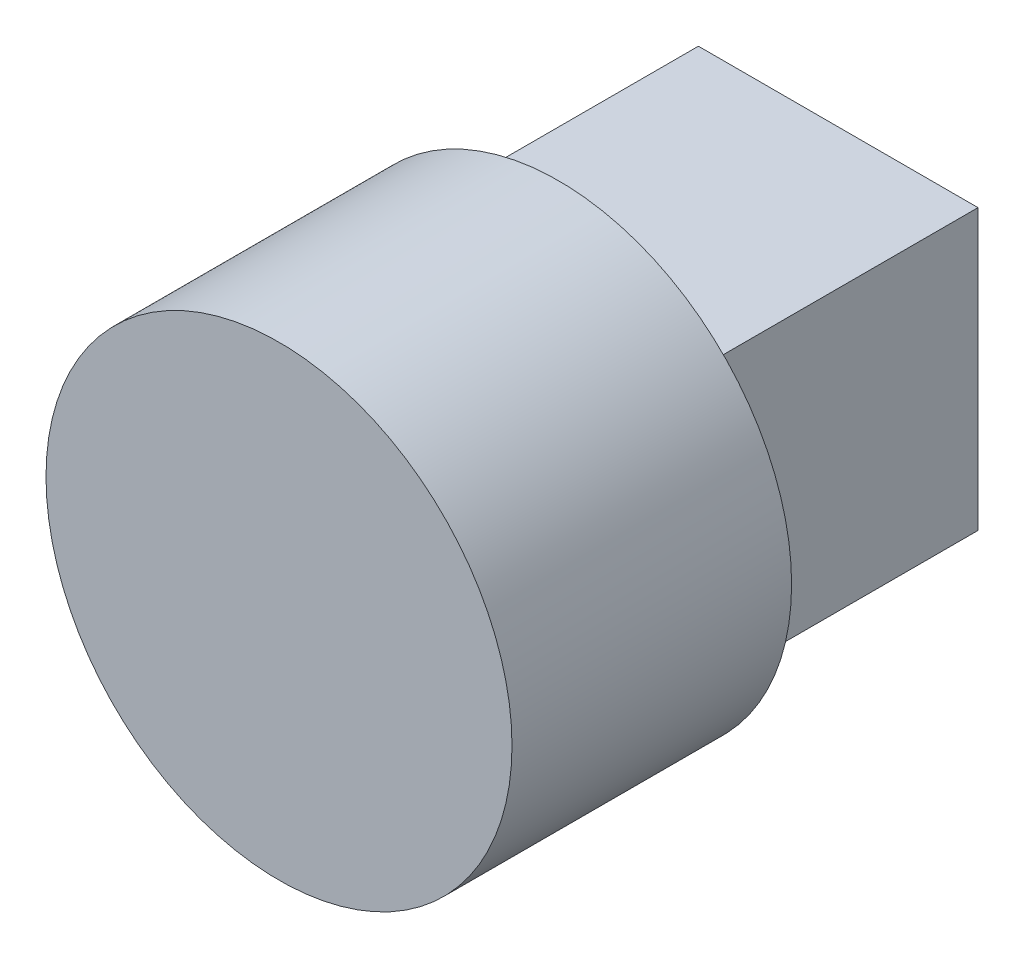
SolidWorks part; units mm, degrees
ref_plane "Front Plane" through (0, 0, 0) normal (0, 0, 1) x (1, 0, 0)
ref_plane "Top Plane" through (0, 0, 0) normal (0, 1, 0) x (1, 0, 0)
ref_plane "Right Plane" through (0, 0, 0) normal (1, 0, 0) x (0, 0, -1)
sketch "Sketch1" plane through (0, 0, 0) normal (0, 0, 1) x (1, 0, 0)
  line L1 (-1.5, 0) -> (-1.5, 1.5)
  line L2 (-1.5, 1.5) -> (1.5, 1.5)
  line L3 (1.5, 1.5) -> (1.5, -1.5)
  line L4 (1.5, -1.5) -> (-1.5, -1.5)
  line L5 (-1.5, -1.5) -> (-1.5, 0)
extrude "Boss-Extrude1" add sketch "Sketch1" along normal blind 3
sketch "Sketch2" plane through (0, 0, 3) normal (0, 0, 1) x (1, 0, 0)
  circle A0 centre (0, 0) radius 2.5
extrude "Boss-Extrude2" add sketch "Sketch2" along normal blind 3
